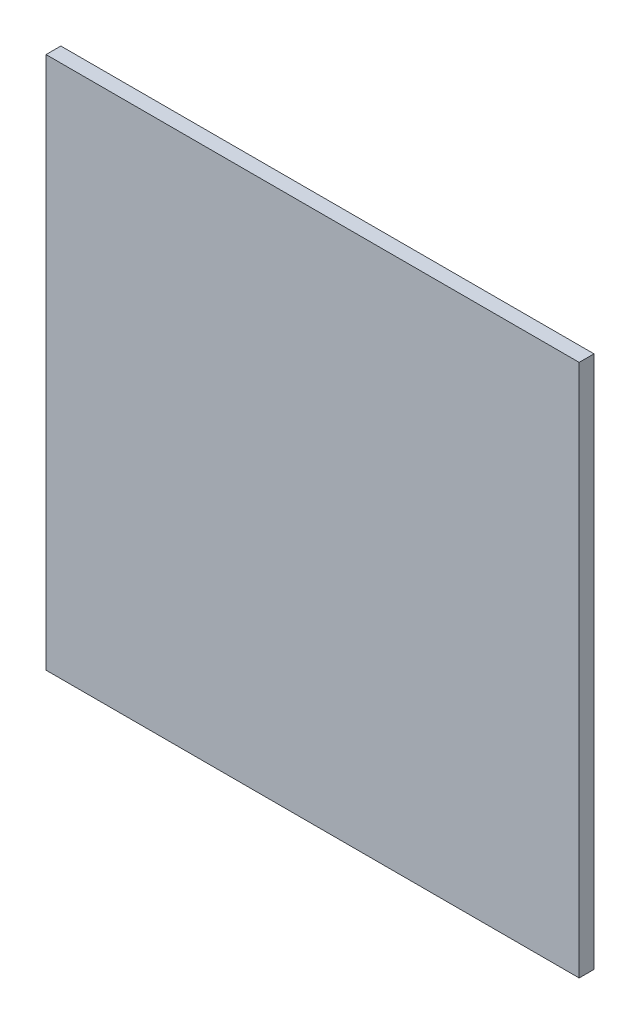
SolidWorks part; units mm, degrees
material "Thornel Mat VMA"
ref_plane "Front Plane" through (0, 0, 0) normal (0, 0, 1) x (1, 0, 0)
ref_plane "Top Plane" through (0, 0, 0) normal (0, 1, 0) x (1, 0, 0)
ref_plane "Right Plane" through (0, 0, 0) normal (1, 0, 0) x (0, 0, -1)
sketch "Sketch1" plane through (0, 0, 0) normal (0, 0, 1) x (1, 0, 0)
  line L1 (-90, -90) -> (90, -90)
  line L2 (-90, -90) -> (-90, 90)
  line L3 (-90, 90) -> (90, 90)
  line L4 (90, -90) -> (90, 90)
  line L5 (-90, -90) -> (90, 90) construction
  line L6 (-90, 90) -> (90, -90) construction
  point P0 (0, 0)
  dimension "D1" = 180
  dimension "D2" = 180
extrude "Boss-Extrude1" add sketch "Sketch1" along normal blind 5
sketch "Sketch2" plane through (0, 0, 0) normal (0, 0, -1) x (-1, 0, 0)
  line L0 (-90, 40) -> (-9.8, 90)
  line L1 (-90, -90) -> (-90, 90) construction
  line L2 (-90, 90) -> (90, 90) construction
  line L3 (-9.8, 90) -> (-90, 90)
  line L4 (-90, 90) -> (-90, 40)
  dimension "D1" = 50
  dimension "D2" = 80.2
